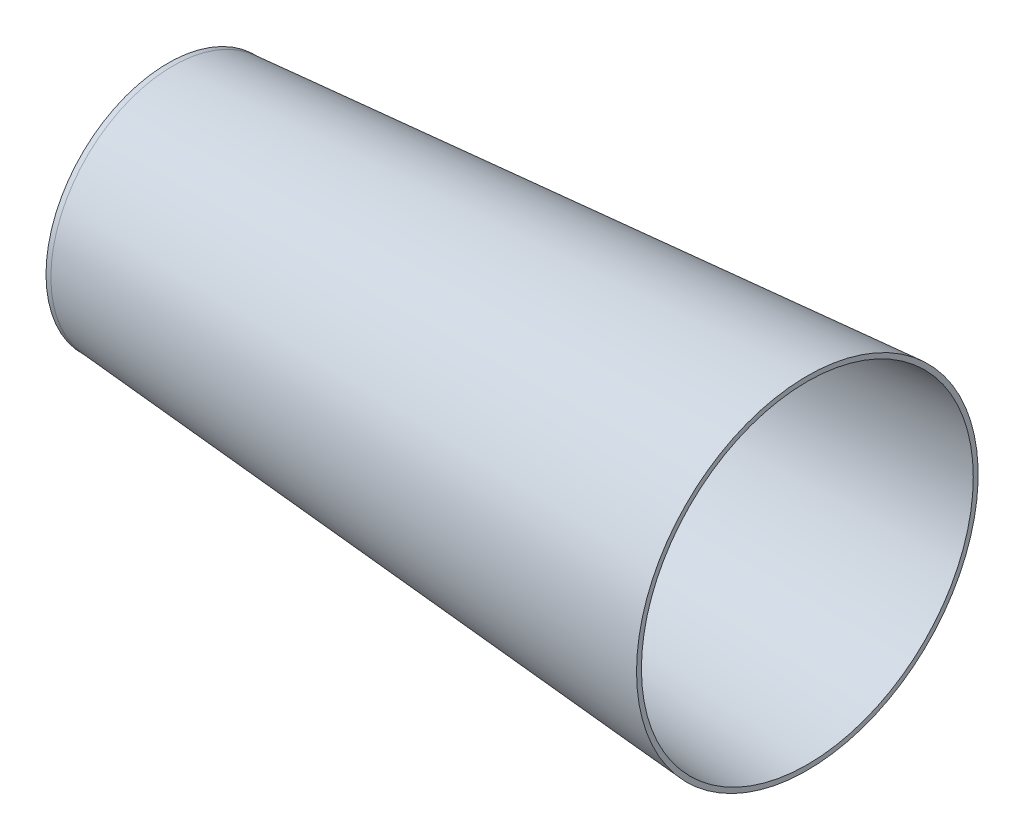
SolidWorks part; units mm, degrees
ref_plane "Plan de face" through (0, 0, 0) normal (0, 0, 1) x (1, 0, 0)
ref_plane "Plan de dessus" through (0, 0, 0) normal (0, 1, 0) x (1, 0, 0)
ref_plane "Plan de droite" through (0, 0, 0) normal (1, 0, 0) x (0, 0, -1)
sketch "Esquisse1" plane through (0, 0, 0) normal (0, 0, 1) x (1, 0, 0)
  line L0 (-48.9485, 0) -> (82.5925, 0) construction
  line L1 (-37.2737, 25) -> (92.7263, 35)
  line L2 (-38.2737, 0) -> (-37.2737, 0)
  line L3 (-38.2737, 0) -> (-38.2737, 25)
  line L4 (-38.2737, 25) -> (-37.2737, 25)
  line L5 (-37.2737, 0) -> (-37.2737, 24)
  line L6 (92.7263, 35) -> (92.7263, 34)
  line L7 (92.7263, 34) -> (-37.2737, 24)
  dimension "D1" = 25
  dimension "D2" = 1
  dimension "D3" = 130
  dimension "D4" = 10
  dimension "D5" = 1
  dimension "D6" = 1
revolve "Révolution1" add sketch "Esquisse1" angle 360 about L0
